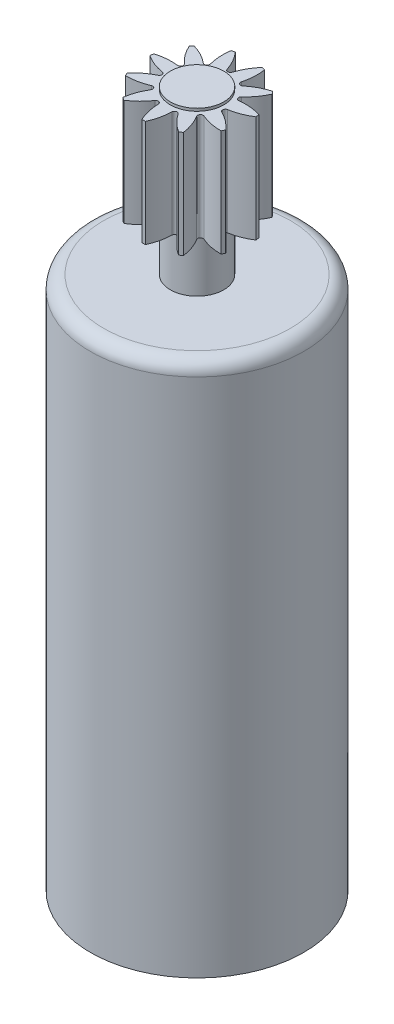
SolidWorks part; units mm, degrees
ref_plane "前视基准面" through (0, 0, 0) normal (0, 0, 1) x (1, 0, 0)
ref_plane "上视基准面" through (0, 0, 0) normal (0, 1, 0) x (1, 0, 0)
ref_plane "右视基准面" through (0, 0, 0) normal (1, 0, 0) x (0, 0, -1)
sketch "草图1" plane through (0, 0, 0) normal (0, 0, 1) x (1, 0, 0)
  line L0 (0, 0) -> (0, 26.1)
  line L1 (0, 26.1) -> (1, 26.1)
  line L2 (1, 26.1) -> (1, 26)
  line L3 (1, 26) -> (2, 26)
  line L4 (2, 26) -> (2, 22)
  line L5 (2, 22) -> (1, 22)
  line L6 (1, 22) -> (1, 20)
  line L7 (1, 20) -> (3.5, 20)
  line L8 (4, 19.5) -> (4, 0)
  line L9 (4, 0) -> (0, 0)
  arc A0 (3.5, 20) -> (4, 19.5) centre (3.5, 19.5) cw
  point P13 (4, 20)
  dimension "D9" = 0.5
  dimension "D1" = 26.1
  dimension "D2" = 1
  dimension "D3" = 0.1
  dimension "D4" = 4
  dimension "D5" = 1
  dimension "D6" = 3
  dimension "D7" = 4
  dimension "D8" = 2
revolve "旋转1" add sketch "草图1" angle 360 about L0
sketch "草图2" plane through (0, 26, 0) normal (0, 1, 0) x (1, 0, 0)
  line L0 (0, 0) -> (0, 2) construction
  circle A0 centre (0, 0) radius 2 construction
  arc A1 (-0.5, 1.9365) -> (0.5, 1.9365) centre (0, 0) ccw
  arc A2 (0.5, 1.9365) -> (0.0953, 1.2198) centre (2.002, 0.6158) ccw
  arc A3 (0.0953, 1.2198) -> (-0.0953, 1.2198) centre (0, 1.25) cw
  arc A4 (-0.5, 1.9365) -> (-0.0953, 1.2198) centre (-2.002, 0.6158) cw
  arc A5 (-0.5, 1.9365) -> (0.5, 1.9365) centre (0, 0) cw
  circle M7 centre (0, 0) radius 2
  dimension "D2" = 2
  dimension "D3" = 0.1
  dimension "D1" = 2
  dimension "D4" = 0.75
extrude "切除-拉伸1" cut sketch "草图2" against normal up to surface (4 mm away) contours L0 A3 A2 M7 | A3 L0 A5 A4 up to face at (0, 22, -2)
pattern_circular "阵列(圆周)1" count 11 over 360 about axis through (0, 0, 0) along (0, 1, 0) of "切除-拉伸1"
